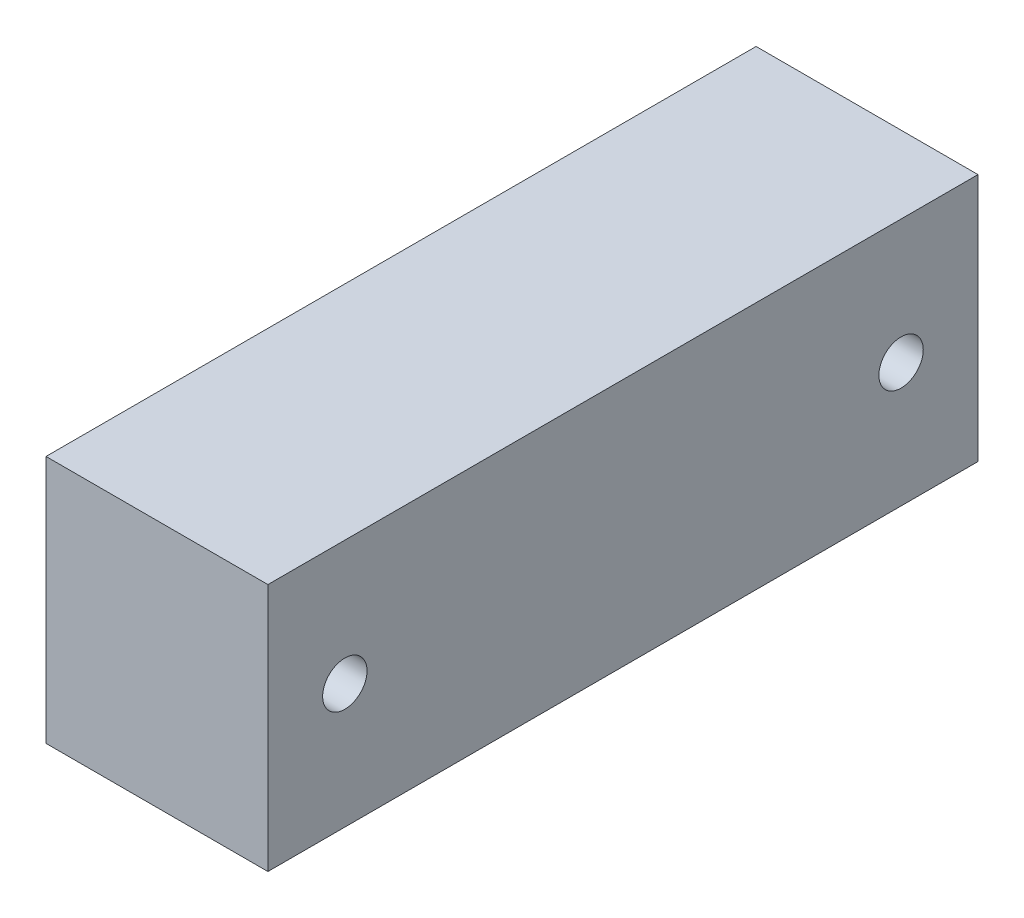
SolidWorks part; units mm, degrees
ref_plane "Alzado" through (0, 0, 0) normal (0, 0, 1) x (1, 0, 0)
ref_plane "Planta" through (0, 0, 0) normal (0, 1, 0) x (1, 0, 0)
ref_plane "Vista lateral" through (0, 0, 0) normal (1, 0, 0) x (0, 0, -1)
sketch "Croquis1" plane through (0, 0, 0) normal (1, 0, 0) x (0, 0, -1)
  line L0 (-18.8, 0) -> (-24, 0) construction
  line L1 (-24, -8.4) -> (24, -8.4)
  line L2 (-24, -8.4) -> (-24, 8.4)
  line L3 (-24, 8.4) -> (24, 8.4)
  line L4 (24, -8.4) -> (24, 8.4)
  line L5 (-24, -8.4) -> (24, 8.4) construction
  line L6 (-24, 8.4) -> (24, -8.4) construction
  line L7 (18.8, 0) -> (24, 0) construction
  circle A0 centre (-18.8, 0) radius 1.5
  circle A1 centre (18.8, 0) radius 1.5
  point P0 (0, 0)
  dimension "D3" = 3
  dimension "D1" = 16.8
  dimension "D2" = 48
  dimension "D4" = 5.2
extrude "Saliente-Extruir1" add sketch "Croquis1" along normal blind 15
